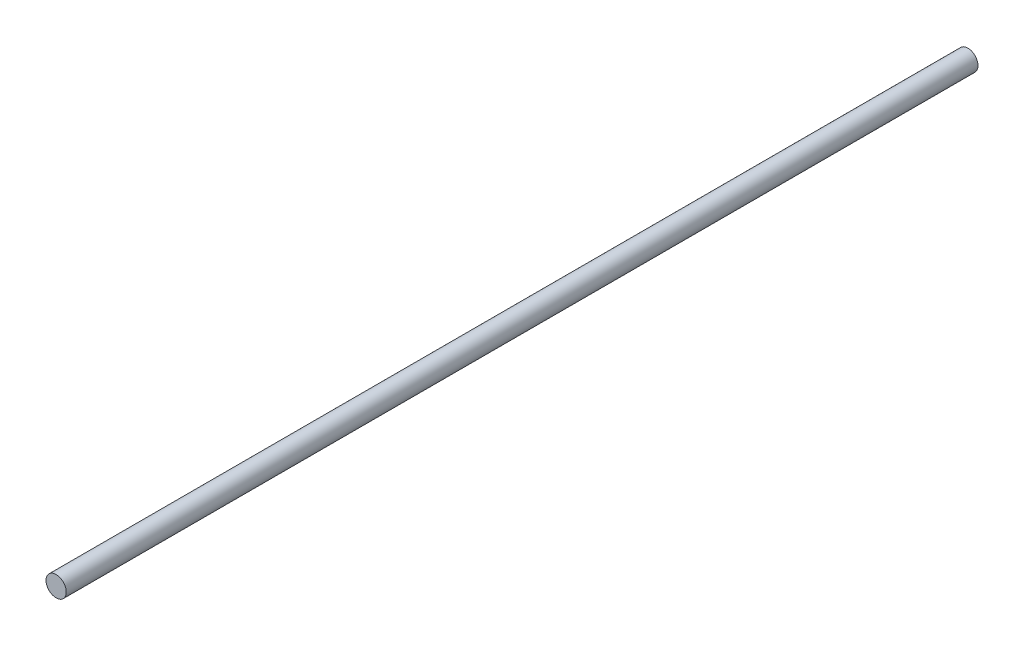
SolidWorks part; units mm, degrees
ref_plane "Спереди" through (0, 0, 0) normal (0, 0, 1) x (1, 0, 0)
ref_plane "Сверху" through (0, 0, 0) normal (0, 1, 0) x (1, 0, 0)
ref_plane "Справа" through (0, 0, 0) normal (1, 0, 0) x (0, 0, -1)
sketch "Эскиз1" plane through (0, 0, 0) normal (0, 0, 1) x (1, 0, 0)
  circle A0 centre (0, 0) radius 4
extrude "Бобышка-Вытянуть1" add sketch "Эскиз1" along normal blind 360
